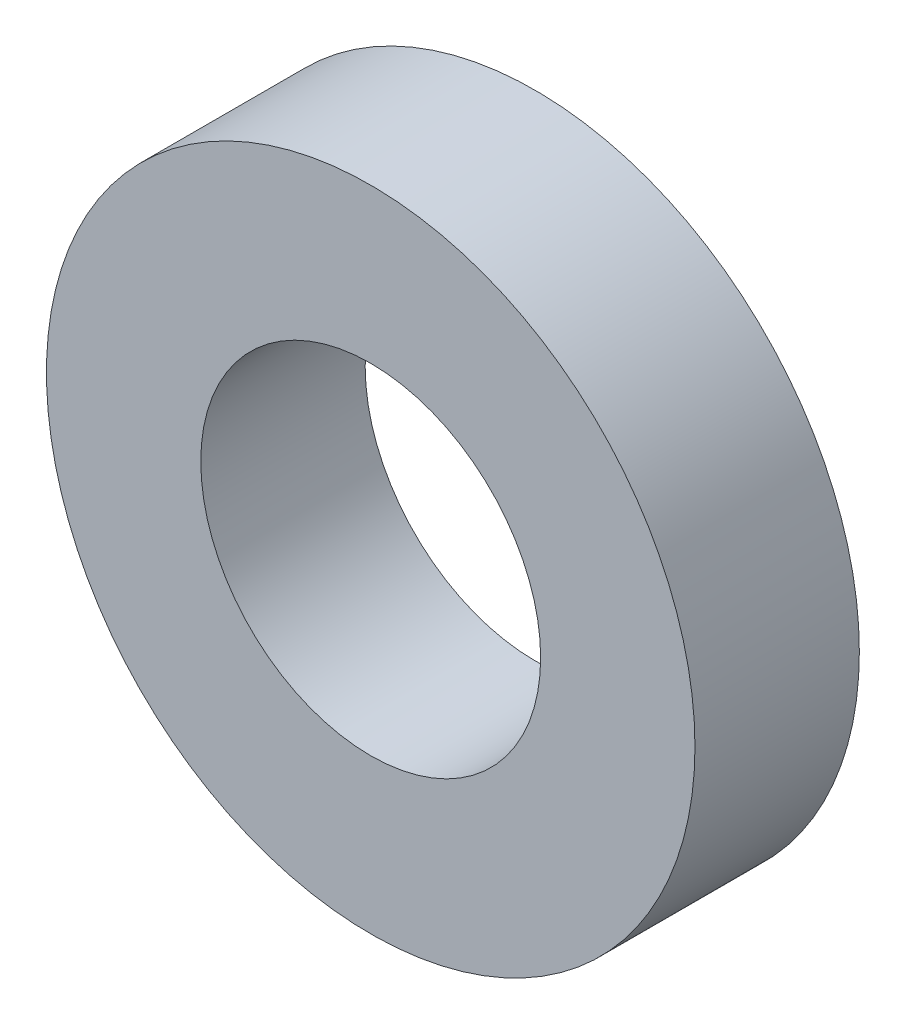
SolidWorks part; units mm, degrees
ref_plane "Plan de face" through (0, 0, 0) normal (1, 0, 0) x (0, 1, 0)
ref_plane "Plan de dessus" through (0, 0, 0) normal (0, 0, 1) x (0, 1, 0)
ref_plane "Plan de droite" through (0, 0, 0) normal (0, 1, 0) x (-1, 0, 0)
sketch "Esquisse1" plane through (0, 0, 0) normal (0, 0, 1) x (0, 1, 0)
  circle A0 centre (0, 0) radius 7.89
  circle A1 centre (0, 0) radius 4.135
  dimension "D1" = 8.27
  dimension "D2" = 15.78
extrude "Boss.-Extru.1" add sketch "Esquisse1" along normal blind 4
